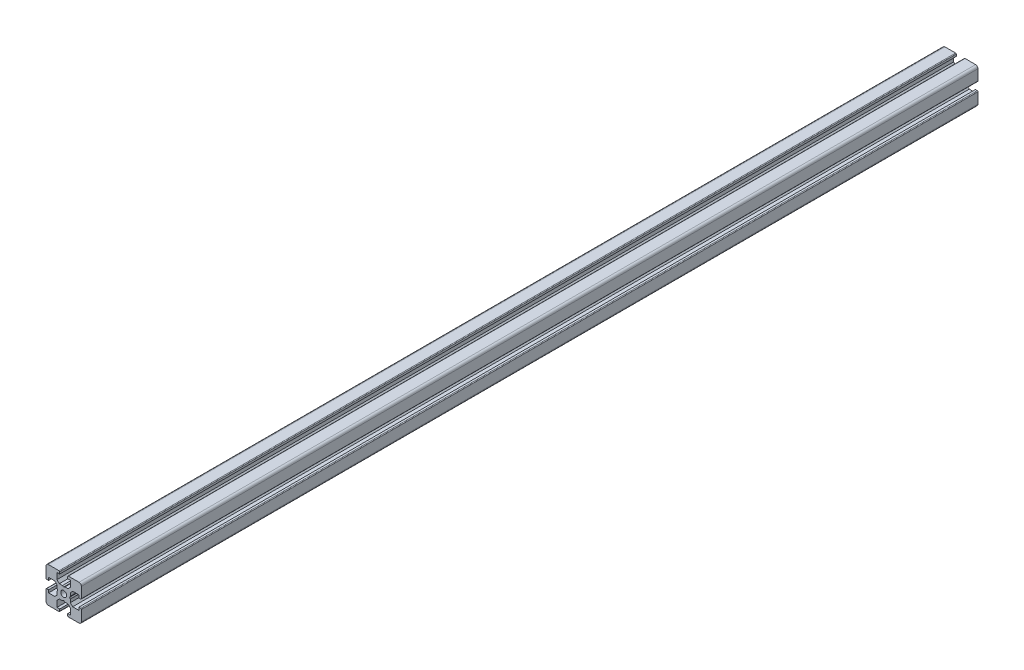
SolidWorks part; units mm, degrees
ref_plane "Front" through (0, 0, 0) normal (0, 0, 1) x (1, 0, 0)
ref_plane "Top" through (0, 0, 0) normal (0, 1, 0) x (1, 0, 0)
ref_plane "Right" through (0, 0, 0) normal (1, 0, 0) x (0, 0, -1)
ref_plane "Plane1" through (0, 0, 0) normal (0, 0, 1) x (1, 0, 0)
sketch "Sketch1" plane through (0, 0, 0) normal (0, 0, 1) x (1, 0, 0)
  line L0 (-7.2, 1.7) -> (-6.4, 1.7)
  line L1 (-6.4, 1.7) -> (-6.4, 2.85)
  line L2 (-6.4, 2.85) -> (-3.8, 2.85)
  line L3 (-3.8, 2.85) -> (-2.8, 1.85)
  line L4 (-2.8, 1.85) -> (-2.8, 0.5196)
  line L5 (-2.8, 0.5196) -> (-2.5, 0)
  line L6 (-2.5, 0) -> (-2.8, -0.5196)
  line L7 (-2.8, -0.5196) -> (-2.8, -1.85)
  line L8 (-2.8, -1.85) -> (-3.8, -2.85)
  line L9 (-3.8, -2.85) -> (-6.4, -2.85)
  line L10 (-6.4, -2.85) -> (-6.4, -1.7)
  line L11 (-6.4, -1.7) -> (-7.2, -1.7)
  line L12 (-7.5, -2) -> (-7.5, -6.5)
  line L13 (-6.5, -7.5) -> (-2, -7.5)
  line L14 (-1.7, -7.2) -> (-1.7, -6.4)
  line L15 (-1.7, -6.4) -> (-2.85, -6.4)
  line L16 (-2.85, -6.4) -> (-2.85, -3.8)
  line L17 (-2.85, -3.8) -> (-1.85, -2.8)
  line L18 (-1.85, -2.8) -> (-0.5196, -2.8)
  line L19 (-0.5196, -2.8) -> (0, -2.5)
  line L20 (0, -2.5) -> (0.5196, -2.8)
  line L21 (0.5196, -2.8) -> (1.85, -2.8)
  line L22 (1.85, -2.8) -> (2.85, -3.8)
  line L23 (2.85, -3.8) -> (2.85, -6.4)
  line L24 (2.85, -6.4) -> (1.7, -6.4)
  line L25 (1.7, -6.4) -> (1.7, -7.2)
  line L26 (2, -7.5) -> (6.5, -7.5)
  line L27 (7.5, -6.5) -> (7.5, -2)
  line L28 (7.2, -1.7) -> (6.4, -1.7)
  line L29 (6.4, -1.7) -> (6.4, -2.85)
  line L30 (6.4, -2.85) -> (3.8, -2.85)
  line L31 (3.8, -2.85) -> (2.8, -1.85)
  line L32 (2.8, -1.85) -> (2.8, -0.5196)
  line L33 (2.8, -0.5196) -> (2.5, 0)
  line L34 (2.5, 0) -> (2.8, 0.5196)
  line L35 (2.8, 0.5196) -> (2.8, 1.85)
  line L36 (2.8, 1.85) -> (3.8, 2.85)
  line L37 (3.8, 2.85) -> (6.4, 2.85)
  line L38 (6.4, 2.85) -> (6.4, 1.7)
  line L39 (6.4, 1.7) -> (7.2, 1.7)
  line L40 (7.5, 2) -> (7.5, 6.5)
  line L41 (6.5, 7.5) -> (2, 7.5)
  line L42 (1.7, 7.2) -> (1.7, 6.4)
  line L43 (1.7, 6.4) -> (2.85, 6.4)
  line L44 (2.85, 6.4) -> (2.85, 3.8)
  line L45 (2.85, 3.8) -> (1.85, 2.8)
  line L46 (1.85, 2.8) -> (0.5196, 2.8)
  line L47 (0.5196, 2.8) -> (0, 2.5)
  line L48 (0, 2.5) -> (-0.5196, 2.8)
  line L49 (-0.5196, 2.8) -> (-1.85, 2.8)
  line L50 (-1.85, 2.8) -> (-2.85, 3.8)
  line L51 (-2.85, 3.8) -> (-2.85, 6.4)
  line L52 (-2.85, 6.4) -> (-1.7, 6.4)
  line L53 (-1.7, 6.4) -> (-1.7, 7.2)
  line L54 (-2, 7.5) -> (-6.5, 7.5)
  line L55 (-7.5, 6.5) -> (-7.5, 2)
  arc A0 (-7.5, 2) -> (-7.2, 1.7) centre (-7.2, 2) ccw
  arc A1 (-7.2, -1.7) -> (-7.5, -2) centre (-7.2, -2) ccw
  arc A2 (-7.5, -6.5) -> (-6.5, -7.5) centre (-6.5, -6.5) ccw
  arc A3 (-2, -7.5) -> (-1.7, -7.2) centre (-2, -7.2) ccw
  arc A4 (1.7, -7.2) -> (2, -7.5) centre (2, -7.2) ccw
  arc A5 (6.5, -7.5) -> (7.5, -6.5) centre (6.5, -6.5) ccw
  arc A6 (7.5, -2) -> (7.2, -1.7) centre (7.2, -2) ccw
  arc A7 (7.2, 1.7) -> (7.5, 2) centre (7.2, 2) ccw
  arc A8 (7.5, 6.5) -> (6.5, 7.5) centre (6.5, 6.5) ccw
  arc A9 (2, 7.5) -> (1.7, 7.2) centre (2, 7.2) ccw
  arc A10 (-1.7, 7.2) -> (-2, 7.5) centre (-2, 7.2) ccw
  arc A11 (-6.5, 7.5) -> (-7.5, 6.5) centre (-6.5, 6.5) ccw
  circle A12 centre (0, 0) radius 1.25
extrude "Boss-Extrude1" add sketch "Sketch1" along normal blind 380
